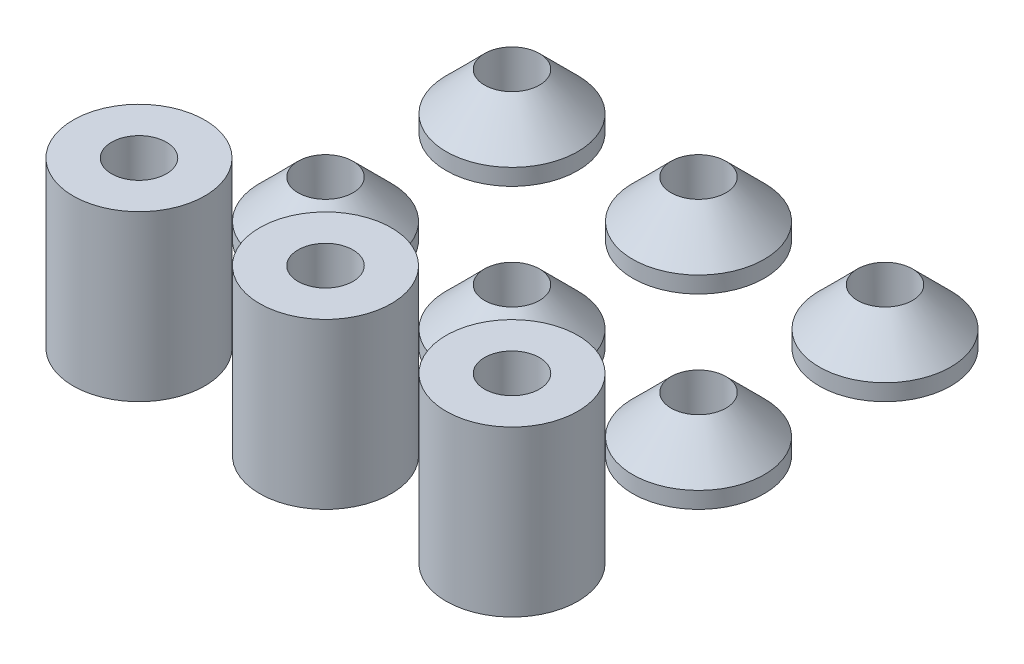
SolidWorks part; units mm, degrees
ref_plane "Alzado" through (0, 0, 0) normal (0, 0, 1) x (1, 0, 0)
ref_plane "Planta" through (0, 0, 0) normal (0, 1, 0) x (1, 0, 0)
ref_plane "Vista lateral" through (0, 0, 0) normal (1, 0, 0) x (0, 0, -1)
sketch "Croquis5" plane through (0, 0, 0) normal (0, 1, 0) x (1, 0, 0)
  line L0 (0, 0) -> (-13.522, 0) construction
  circle A0 centre (-13.522, 0) radius 6
  dimension "D1" = 12
extrude "Saliente-Extruir3" add sketch "Croquis5" along normal blind 4 separate body
sketch "Croquis6" plane through (0, 4, 0) normal (0, 1, 0) x (1, 0, 0)
  circle A0 centre (-13.522, 0) radius 2.5
  dimension "D1" = 5
extrude "Cortar-Extruir3" cut sketch "Croquis6" against normal blind 4
sketch "Croquis7" plane through (0, 4, 0) normal (0, 1, 0) x (1, 0, 0)
  line L0 (-13.522, 0) -> (-15.9753, -0.4809) construction
  line L1 (-15.9753, -0.4809) -> (-16.9566, -0.6733) construction
  circle A0 centre (-13.522, 0) radius 2.5
  circle A1 centre (-13.522, 0) radius 3.5
  circle A4 centre (-13.522, 0) radius 2.5 construction
  dimension "D1" = 1
extrude "Saliente-Extruir4" add sketch "Croquis7" along normal blind 1
ref_axis "Eje1" through (-13.522, 0, 0) along (0, 1, 0)
sketch "Croquis9" plane through (0, 0, 0) normal (0, 0, 1) x (1, 0, 0)
  line L0 (-19.522, 1.5) -> (-16.022, 5)
  line L1 (-16.022, 5) -> (-19.522, 5)
  line L2 (-19.522, 5) -> (-19.522, 1.5)
  line L3 (-11.022, 5) -> (-16.022, 5) construction
  line L5 (-19.522, 4) -> (-19.522, 0) construction
  dimension "D1" = 3.5
revolve "Cortar-Revolución4" cut sketch "Croquis9" angle 360 about axis through (-13.522, 0, 0) along (0, 1, 0)
sketch "Croquis10" plane through (0, 0, 0) normal (0, 1, 0) x (1, 0, 0)
  line L0 (-13.522, 0) -> (-13.522, -17) construction
  line L1 (-13.522, 0) -> (3.478, 0) construction
  line L2 (-13.522, -17) -> (-13.522, -34) construction
  dimension "D1" = 17
  dimension "D2" = 17
  dimension "D3" = 17
pattern_linear "MatrizL1" count 3 spacing 17 along (1, 0, 0) count 2 spacing 17 along (0, 0, 1) of bodies 121
sketch "Croquis11" plane through (0, 0, 0) normal (0, 1, 0) x (1, 0, 0)
  circle A0 centre (-13.522, -34) radius 6
  circle A1 centre (-13.522, -34) radius 2.5
  dimension "D1" = 5
  dimension "D2" = 12
extrude "Saliente-Extruir5" add sketch "Croquis11" along normal blind 15 separate body
pattern_linear "MatrizL2" count 3 spacing 17 along (1, 0, 0) of "Saliente-Extruir5"
